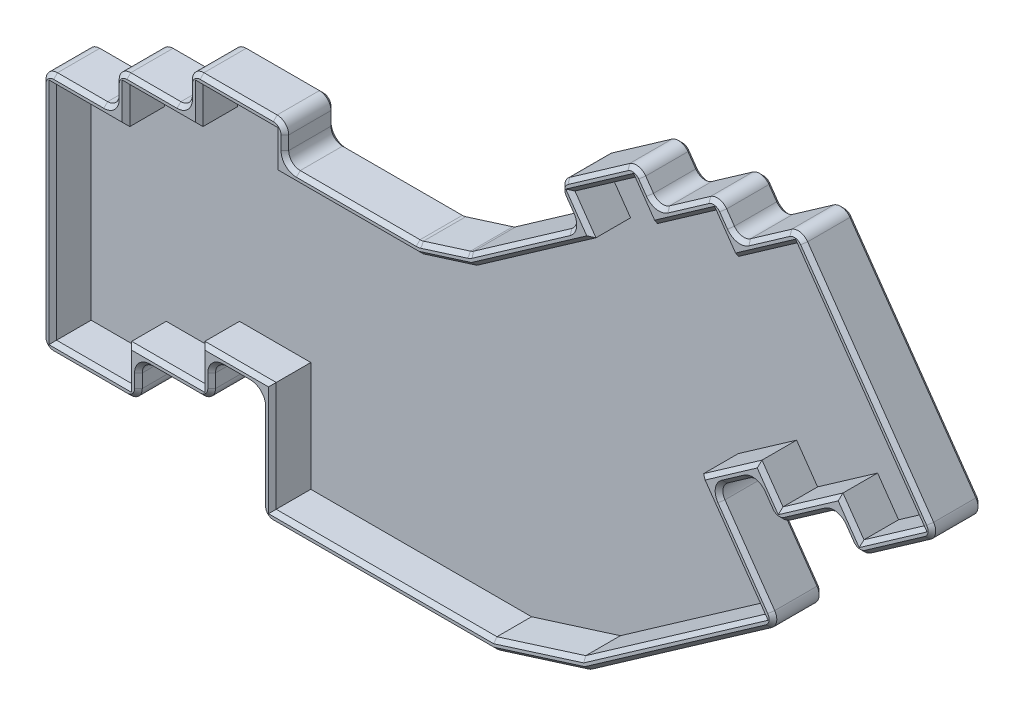
SolidWorks part; units mm, degrees
ref_plane "Front Plane" through (0, 0, 0) normal (0, 0, 1) x (1, 0, 0)
ref_plane "Top Plane" through (0, 0, 0) normal (0, 1, 0) x (1, 0, 0)
ref_plane "Right Plane" through (0, 0, 0) normal (1, 0, 0) x (0, 0, -1)
sketch "Sketch1" plane through (0, 0, 0) normal (0, 0, 1) x (1, 0, 0)
  line L64 (57.15, -66.675) -> (114.3, -66.675)
  line L65 (114.3, -66.675) -> (137.3388, -59.4109)
  line L66 (137.3388, -59.4109) -> (184.1534, -26.631)
  line L67 (184.1534, -26.631) -> (167.7634, -3.2237)
  line L68 (167.7634, -3.2237) -> (183.3683, 7.7029)
  line L69 (183.3683, 7.7029) -> (188.8316, -0.0995)
  line L70 (188.8316, -0.0995) -> (204.4364, 10.8271)
  line L71 (204.4364, 10.8271) -> (209.8998, 3.0247)
  line L72 (209.8998, 3.0247) -> (225.5046, 13.9513)
  line L73 (225.5046, 13.9513) -> (192.7247, 60.7659)
  line L74 (192.7247, 60.7659) -> (177.1199, 49.8392)
  line L75 (177.1199, 49.8392) -> (171.6565, 57.6417)
  line L76 (171.6565, 57.6417) -> (156.0517, 46.715)
  line L77 (156.0517, 46.715) -> (150.5884, 54.5175)
  line L78 (150.5884, 54.5175) -> (134.9835, 43.5908)
  line L79 (134.9835, 43.5908) -> (140.4469, 35.7884)
  line L80 (140.4469, 35.7884) -> (109.2372, 13.9351)
  line L81 (109.2372, 13.9351) -> (95.25, 9.525)
  line L82 (95.25, 9.525) -> (57.15, 9.525)
  line L83 (57.15, 9.525) -> (57.15, 19.05)
  line L84 (57.15, 19.05) -> (38.1, 19.05)
  line L85 (38.1, 19.05) -> (38.1, 9.525)
  line L86 (38.1, 9.525) -> (19.05, 9.525)
  line L87 (19.05, 9.525) -> (19.05, 0)
  line L88 (19.05, 0) -> (0, 0)
  line L89 (0, 0) -> (0, -57.15)
  line L90 (0, -57.15) -> (19.05, -57.15)
  line L91 (19.05, -57.15) -> (19.05, -47.625)
  line L92 (19.05, -47.625) -> (38.1, -47.625)
  line L93 (38.1, -47.625) -> (38.1, -38.1)
  line L94 (38.1, -38.1) -> (57.15, -38.1)
  line L95 (57.15, -38.1) -> (57.15, -66.675)
extrude "Boss-Extrude1" add sketch "Sketch1" along normal blind 3 contours L82 L83 L84 L85 L86 L87 L88 L89 L90 L91 L92 L93 L94 L95 L64 L65 L66 L67 L68 L69 L70 L71 L72 L73 L74 L75 L76 L77 L78 L79 L80 L81
sketch "Sketch2" plane through (0, 0, 3) normal (0, 0, 1) x (1, 0, 0)
  line L64 (107.8947, 16.6574) -> (94.7883, 12.525)
  line L65 (94.7883, 12.525) -> (60.15, 12.525)
  line L66 (60.15, 12.525) -> (60.15, 22.05)
  line L67 (60.15, 22.05) -> (35.1, 22.05)
  line L68 (35.1, 22.05) -> (35.1, 12.525)
  line L69 (35.1, 12.525) -> (16.05, 12.525)
  line L70 (16.05, 12.525) -> (16.05, 3)
  line L71 (16.05, 3) -> (-3, 3)
  line L72 (-3, 3) -> (-3, -60.15)
  line L73 (-3, -60.15) -> (22.05, -60.15)
  line L74 (22.05, -60.15) -> (22.05, -50.625)
  line L75 (22.05, -50.625) -> (41.1, -50.625)
  line L76 (41.1, -50.625) -> (41.1, -41.1)
  line L77 (41.1, -41.1) -> (54.15, -41.1)
  line L78 (54.15, -41.1) -> (54.15, -69.675)
  line L79 (54.15, -69.675) -> (114.7617, -69.675)
  line L80 (114.7617, -69.675) -> (138.6813, -62.1332)
  line L81 (138.6813, -62.1332) -> (188.3316, -27.3677)
  line L82 (188.3316, -27.3677) -> (171.9416, -3.9604)
  line L83 (171.9416, -3.9604) -> (182.6315, 3.5247)
  line L84 (182.6315, 3.5247) -> (188.0949, -4.2777)
  line L85 (188.0949, -4.2777) -> (203.6997, 6.6489)
  line L86 (203.6997, 6.6489) -> (209.163, -1.1535)
  line L87 (209.163, -1.1535) -> (229.6828, 13.2146)
  line L88 (229.6828, 13.2146) -> (193.4614, 64.9441)
  line L89 (193.4614, 64.9441) -> (177.8566, 54.0174)
  line L90 (177.8566, 54.0174) -> (172.3933, 61.8198)
  line L91 (172.3933, 61.8198) -> (156.7884, 50.8932)
  line L92 (156.7884, 50.8932) -> (151.3251, 58.6956)
  line L93 (151.3251, 58.6956) -> (130.8054, 44.3275)
  line L94 (130.8054, 44.3275) -> (136.2687, 36.5251)
  line L95 (136.2687, 36.5251) -> (107.8947, 16.6574)
  line L96 (107.8947, 16.6574) -> (94.7883, 12.525)
  line L97 (94.7883, 12.525) -> (60.15, 12.525)
  line L98 (60.15, 12.525) -> (60.15, 22.05)
  line L99 (60.15, 22.05) -> (35.1, 22.05)
  line L100 (35.1, 22.05) -> (35.1, 12.525)
  line L101 (35.1, 12.525) -> (16.05, 12.525)
  line L102 (16.05, 12.525) -> (16.05, 3)
  line L103 (16.05, 3) -> (-3, 3)
  line L104 (-3, 3) -> (-3, -60.15)
  line L105 (-3, -60.15) -> (22.05, -60.15)
  line L106 (22.05, -60.15) -> (22.05, -50.625)
  line L107 (22.05, -50.625) -> (41.1, -50.625)
  line L108 (41.1, -50.625) -> (41.1, -41.1)
  line L109 (41.1, -41.1) -> (54.15, -41.1)
  line L110 (54.15, -41.1) -> (54.15, -69.675)
  line L111 (54.15, -69.675) -> (114.7617, -69.675)
  line L112 (114.7617, -69.675) -> (138.6813, -62.1332)
  line L113 (138.6813, -62.1332) -> (188.3316, -27.3677)
  line L114 (188.3316, -27.3677) -> (171.9416, -3.9604)
  line L115 (171.9416, -3.9604) -> (182.6315, 3.5247)
  line L116 (182.6315, 3.5247) -> (188.0949, -4.2777)
  line L117 (188.0949, -4.2777) -> (203.6997, 6.6489)
  line L118 (203.6997, 6.6489) -> (209.163, -1.1535)
  line L119 (209.163, -1.1535) -> (229.6828, 13.2146)
  line L120 (229.6828, 13.2146) -> (193.4614, 64.9441)
  line L121 (193.4614, 64.9441) -> (177.8566, 54.0174)
  line L122 (177.8566, 54.0174) -> (172.3933, 61.8198)
  line L123 (172.3933, 61.8198) -> (156.7884, 50.8932)
  line L124 (156.7884, 50.8932) -> (151.3251, 58.6956)
  line L125 (151.3251, 58.6956) -> (130.8054, 44.3275)
  line L126 (130.8054, 44.3275) -> (136.2687, 36.5251)
  line L127 (136.2687, 36.5251) -> (107.8947, 16.6574)
  line L128 (109.2372, 13.9351) -> (95.25, 9.525)
  line L129 (95.25, 9.525) -> (57.15, 9.525)
  line L130 (57.15, 9.525) -> (57.15, 19.05)
  line L131 (57.15, 19.05) -> (38.1, 19.05)
  line L132 (38.1, 19.05) -> (38.1, 9.525)
  line L133 (38.1, 9.525) -> (19.05, 9.525)
  line L134 (19.05, 9.525) -> (19.05, 0)
  line L135 (19.05, 0) -> (0, 0)
  line L136 (0, 0) -> (0, -57.15)
  line L137 (0, -57.15) -> (19.05, -57.15)
  line L138 (19.05, -57.15) -> (19.05, -47.625)
  line L139 (19.05, -47.625) -> (38.1, -47.625)
  line L140 (38.1, -47.625) -> (38.1, -38.1)
  line L141 (38.1, -38.1) -> (57.15, -38.1)
  line L142 (57.15, -38.1) -> (57.15, -66.675)
  line L143 (57.15, -66.675) -> (114.3, -66.675)
  line L144 (114.3, -66.675) -> (137.3388, -59.4109)
  line L145 (137.3388, -59.4109) -> (184.1534, -26.631)
  line L146 (184.1534, -26.631) -> (167.7634, -3.2237)
  line L147 (167.7634, -3.2237) -> (183.3683, 7.7029)
  line L148 (183.3683, 7.7029) -> (188.8316, -0.0995)
  line L149 (188.8316, -0.0995) -> (204.4364, 10.8271)
  line L150 (204.4364, 10.8271) -> (209.8998, 3.0247)
  line L151 (209.8998, 3.0247) -> (225.5046, 13.9513)
  line L152 (225.5046, 13.9513) -> (192.7247, 60.7659)
  line L153 (192.7247, 60.7659) -> (177.1199, 49.8392)
  line L154 (177.1199, 49.8392) -> (171.6565, 57.6417)
  line L155 (171.6565, 57.6417) -> (156.0517, 46.715)
  line L156 (156.0517, 46.715) -> (150.5884, 54.5175)
  line L157 (150.5884, 54.5175) -> (134.9835, 43.5908)
  line L158 (134.9835, 43.5908) -> (140.4469, 35.7884)
  line L159 (140.4469, 35.7884) -> (109.2372, 13.9351)
  line L160 (109.2372, 13.9351) -> (95.25, 9.525)
  line L161 (95.25, 9.525) -> (57.15, 9.525)
  line L162 (57.15, 9.525) -> (57.15, 19.05)
  line L163 (57.15, 19.05) -> (38.1, 19.05)
  line L164 (38.1, 19.05) -> (38.1, 9.525)
  line L165 (38.1, 9.525) -> (19.05, 9.525)
  line L166 (19.05, 9.525) -> (19.05, 0)
  line L167 (19.05, 0) -> (0, 0)
  line L168 (0, 0) -> (0, -57.15)
  line L169 (0, -57.15) -> (19.05, -57.15)
  line L170 (19.05, -57.15) -> (19.05, -47.625)
  line L171 (19.05, -47.625) -> (38.1, -47.625)
  line L172 (38.1, -47.625) -> (38.1, -38.1)
  line L173 (38.1, -38.1) -> (57.15, -38.1)
  line L174 (57.15, -38.1) -> (57.15, -66.675)
  line L175 (57.15, -66.675) -> (114.3, -66.675)
  line L176 (114.3, -66.675) -> (137.3388, -59.4109)
  line L177 (137.3388, -59.4109) -> (184.1534, -26.631)
  line L178 (184.1534, -26.631) -> (167.7634, -3.2237)
  line L179 (167.7634, -3.2237) -> (183.3683, 7.7029)
  line L180 (183.3683, 7.7029) -> (188.8316, -0.0995)
  line L181 (188.8316, -0.0995) -> (204.4364, 10.8271)
  line L182 (204.4364, 10.8271) -> (209.8998, 3.0247)
  line L183 (209.8998, 3.0247) -> (225.5046, 13.9513)
  line L184 (225.5046, 13.9513) -> (192.7247, 60.7659)
  line L185 (192.7247, 60.7659) -> (177.1199, 49.8392)
  line L186 (177.1199, 49.8392) -> (171.6565, 57.6417)
  line L187 (171.6565, 57.6417) -> (156.0517, 46.715)
  line L188 (156.0517, 46.715) -> (150.5884, 54.5175)
  line L189 (150.5884, 54.5175) -> (134.9835, 43.5908)
  line L190 (134.9835, 43.5908) -> (140.4469, 35.7884)
  line L191 (140.4469, 35.7884) -> (109.2372, 13.9351)
  dimension "D1" = 3
  dimension "D2" = 0
extrude "Boss-Extrude2" add sketch "Sketch2" along normal blind 13 from surface at -3 starting at face at (106.2767, -1.0614, 0)
fillet "Fillet1" radius 3 32 edges at (114.7617, -69.675, 6.5) (94.7883, 12.525, 6.5) (60.15, 12.525, 6.5) (60.15, 22.05, 6.5) (35.1, 22.05, 6.5) (35.1, 12.525, 6.5) (16.05, 12.525, 6.5) (16.05, 3, 6.5) (-3, 3, 6.5) (-3, -60.15, 6.5) (22.05, -60.15, 6.5) (22.05, -50.625, 6.5) (41.1, -50.625, 6.5) (41.1, -41.1, 6.5) (54.15, -69.675, 6.5) (54.15, -41.1, 6.5) (107.8947, 16.6574, 6.5) (136.2687, 36.5251, 6.5) (130.8054, 44.3275, 6.5) (151.3251, 58.6956, 6.5) (156.7884, 50.8932, 6.5) (172.3933, 61.8198, 6.5) (177.8566, 54.0174, 6.5) (193.4614, 64.9441, 6.5) (229.6828, 13.2146, 6.5) (209.163, -1.1535, 6.5) (203.6997, 6.6489, 6.5) (188.0949, -4.2777, 6.5) (182.6315, 3.5247, 6.5) (171.9416, -3.9604, 6.5) (188.3316, -27.3677, 6.5) (138.6813, -62.1332, 6.5)
sketch "Sketch3" plane through (0, 0, 13) normal (0, 0, 1) x (1, 0, 0)
  line L32 (109.2372, 13.9351) -> (95.25, 9.525)
  line L33 (95.25, 9.525) -> (57.15, 9.525)
  line L34 (57.15, 9.525) -> (57.15, 19.05)
  line L35 (57.15, 19.05) -> (38.1, 19.05)
  line L36 (38.1, 19.05) -> (38.1, 9.525)
  line L37 (38.1, 9.525) -> (19.05, 9.525)
  line L38 (19.05, 9.525) -> (19.05, 0)
  line L39 (19.05, 0) -> (0, 0)
  line L40 (0, 0) -> (0, -57.15)
  line L41 (0, -57.15) -> (19.05, -57.15)
  line L42 (19.05, -57.15) -> (19.05, -47.625)
  line L43 (19.05, -47.625) -> (38.1, -47.625)
  line L44 (38.1, -47.625) -> (38.1, -38.1)
  line L45 (38.1, -38.1) -> (57.15, -38.1)
  line L46 (57.15, -38.1) -> (57.15, -66.675)
  line L47 (57.15, -66.675) -> (114.3, -66.675)
  line L48 (114.3, -66.675) -> (137.3388, -59.4109)
  line L49 (137.3388, -59.4109) -> (184.1534, -26.631)
  line L50 (184.1534, -26.631) -> (167.7634, -3.2237)
  line L51 (167.7634, -3.2237) -> (183.3683, 7.7029)
  line L52 (183.3683, 7.7029) -> (188.8316, -0.0995)
  line L53 (188.8316, -0.0995) -> (204.4364, 10.8271)
  line L54 (204.4364, 10.8271) -> (209.8998, 3.0247)
  line L55 (209.8998, 3.0247) -> (225.5046, 13.9513)
  line L56 (225.5046, 13.9513) -> (192.7247, 60.7659)
  line L57 (192.7247, 60.7659) -> (177.1199, 49.8392)
  line L58 (177.1199, 49.8392) -> (171.6565, 57.6417)
  line L59 (171.6565, 57.6417) -> (156.0517, 46.715)
  line L60 (156.0517, 46.715) -> (150.5884, 54.5175)
  line L61 (150.5884, 54.5175) -> (134.9835, 43.5908)
  line L62 (134.9835, 43.5908) -> (140.4469, 35.7884)
  line L63 (140.4469, 35.7884) -> (109.2372, 13.9351)
  line L64 (109.2372, 13.9351) -> (95.25, 9.525)
  line L65 (95.25, 9.525) -> (57.15, 9.525)
  line L66 (57.15, 9.525) -> (57.15, 19.05)
  line L67 (57.15, 19.05) -> (38.1, 19.05)
  line L68 (38.1, 19.05) -> (38.1, 9.525)
  line L69 (38.1, 9.525) -> (19.05, 9.525)
  line L70 (19.05, 9.525) -> (19.05, 0)
  line L71 (19.05, 0) -> (0, 0)
  line L72 (0, 0) -> (0, -57.15)
  line L73 (0, -57.15) -> (19.05, -57.15)
  line L74 (19.05, -57.15) -> (19.05, -47.625)
  line L75 (19.05, -47.625) -> (38.1, -47.625)
  line L76 (38.1, -47.625) -> (38.1, -38.1)
  line L77 (38.1, -38.1) -> (57.15, -38.1)
  line L78 (57.15, -38.1) -> (57.15, -66.675)
  line L79 (57.15, -66.675) -> (114.3, -66.675)
  line L80 (114.3, -66.675) -> (137.3388, -59.4109)
  line L81 (137.3388, -59.4109) -> (184.1534, -26.631)
  line L82 (184.1534, -26.631) -> (167.7634, -3.2237)
  line L83 (167.7634, -3.2237) -> (183.3683, 7.7029)
  line L84 (183.3683, 7.7029) -> (188.8316, -0.0995)
  line L85 (188.8316, -0.0995) -> (204.4364, 10.8271)
  line L86 (204.4364, 10.8271) -> (209.8998, 3.0247)
  line L87 (209.8998, 3.0247) -> (225.5046, 13.9513)
  line L88 (225.5046, 13.9513) -> (192.7247, 60.7659)
  line L89 (192.7247, 60.7659) -> (177.1199, 49.8392)
  line L90 (177.1199, 49.8392) -> (171.6565, 57.6417)
  line L91 (171.6565, 57.6417) -> (156.0517, 46.715)
  line L92 (156.0517, 46.715) -> (150.5884, 54.5175)
  line L93 (150.5884, 54.5175) -> (134.9835, 43.5908)
  line L94 (134.9835, 43.5908) -> (140.4469, 35.7884)
  line L95 (140.4469, 35.7884) -> (109.2372, 13.9351)
  dimension "D1" = 0
extrude "Cut-Extrude-Thin3" cut sketch "Sketch3" against normal up to surface (10 mm away) thin
chamfer "Chamfer1" distance 1 angle 45 160 edges at (135.0449, 36.7409, 0) (121.0421, 25.8633, 0) (121.0421, 25.8633, 13) (107.879, 16.6891, 0) (101.3415, 14.5912, 13) (101.3415, 14.5912, 0) (94.7829, 12.5599, 0) (78.7383, 12.525, 13) (78.7383, 12.525, 0) (61.0287, 13.4037, 0) (60.15, 17.2875, 13) (60.15, 17.2875, 0) (59.2713, 21.1713, 0) (47.625, 22.05, 13) (47.625, 22.05, 0) (35.9787, 21.1713, 0) (35.1, 17.2875, 13) (35.1, 17.2875, 0) (34.2213, 13.4037, 0) (25.575, 12.525, 13) (25.575, 12.525, 0) (16.9287, 11.6463, 0) (16.05, 7.7625, 13) (16.05, 7.7625, 0) (15.1713, 3.8787, 0) (6.525, 3, 13) (6.525, 3, 0) (-2.1213, 2.1213, 0) (-3, -28.575, 13) (-3, -28.575, 0) (-2.1213, -59.2713, 0) (9.525, -60.15, 13) (9.525, -60.15, 0) (21.1713, -59.2713, 0) (22.05, -55.3875, 13) (22.05, -55.3875, 0) (22.9287, -51.5037, 0) (31.575, -50.625, 13) (31.575, -50.625, 0) (40.2213, -49.7463, 0) (41.1, -45.8625, 13) (41.1, -45.8625, 0) (41.9787, -41.9787, 0) (47.625, -41.1, 13) (47.625, -41.1, 0) (53.2713, -41.9787, 0) (54.15, -55.3875, 0) (54.15, -55.3875, 13) (55.0287, -68.7963, 0) (85.725, -69.675, 0) (85.725, -69.675, 13) (114.7564, -69.6401, 0) (126.7215, -65.9041, 0) (126.7215, -65.9041, 13) (138.6657, -62.1015, 0) (162.4668, -45.4784, 0) (162.4668, -45.4784, 13) (187.1078, -27.1519, 0) (180.1366, -15.6641, 0) (180.1366, -15.6641, 13) (173.1654, -4.1762, 0) (177.2866, -0.2179, 0) (177.2866, -0.2179, 13) (182.4158, 2.301, 0) (185.3632, -0.3765, 0) (185.3632, -0.3765, 13) (188.3106, -3.0539, 0) (195.8973, 1.1856, 0) (195.8973, 1.1856, 13) (203.4839, 5.4252, 0) (206.4314, 2.7477, 0) (206.4314, 2.7477, 13) (209.3788, 0.0703, 0) (219.4229, 6.0306, 0) (219.4229, 6.0306, 13) (228.459, 13.4304, 0) (211.5721, 39.0793, 0) (211.5721, 39.0793, 13) (193.2457, 63.7203, 0) (185.659, 59.4807, 0) (185.659, 59.4807, 13) (178.0724, 55.2412, 0) (175.1249, 57.9186, 0) (175.1249, 57.9186, 13) (172.1775, 60.5961, 0) (164.5908, 56.3565, 0) (164.5908, 56.3565, 13) (157.0042, 52.117, 0) (154.0568, 54.7944, 0) (154.0568, 54.7944, 13) (151.1093, 57.4719, 0) (141.0652, 51.5116, 0) (141.0652, 51.5116, 13) (132.0291, 44.1118, 0) (133.537, 40.4263, 0) (133.537, 40.4263, 13) (151.1093, 57.4719, 13) (157.0042, 52.117, 13) (172.1775, 60.5961, 13) (178.0724, 55.2412, 13) (193.2457, 63.7203, 13) (228.459, 13.4304, 13) (209.3788, 0.0703, 13) (203.4839, 5.4252, 13) (188.3106, -3.0539, 13) (182.4158, 2.301, 13) (173.1654, -4.1762, 13) (187.1078, -27.1519, 13) (138.6657, -62.1015, 13) (114.7564, -69.6401, 13) (55.0287, -68.7963, 13) (53.2713, -41.9787, 13) (41.9787, -41.9787, 13) (40.2213, -49.7463, 13) (22.9287, -51.5037, 13) (21.1713, -59.2713, 13) (-2.1213, -59.2713, 13) (-2.1213, 2.1213, 13) (15.1713, 3.8787, 13) (16.9287, 11.6463, 13) (34.2213, 13.4037, 13) (35.9787, 21.1713, 13) (59.2713, 21.1713, 13) (61.0287, 13.4037, 13) (94.7829, 12.5599, 13) (107.879, 16.6891, 13) (135.0449, 36.7409, 13) (132.0291, 44.1118, 13) (76.3058, 9.775, 13) (57.4, 14.5375, 13) (47.625, 19.3, 13) (37.85, 14.5375, 13) (28.325, 9.775, 13) (18.8, 5.0125, 13) (9.275, 0.25, 13) (-0.25, -28.575, 13) (9.525, -57.4, 13) (19.3, -52.6375, 13) (28.825, -47.875, 13) (38.35, -43.1125, 13) (47.625, -38.35, 13) (56.9, -52.6375, 13) (85.6192, -66.925, 13) (125.8946, -63.2814, 13) (160.9761, -43.1651, 13) (176.3066, -14.9887, 13) (175.7092, 2.0348, 13) (186.0385, 3.4535, 13) (196.5726, 5.0156, 13) (207.1067, 6.5777, 13) (217.8456, 8.2832, 13) (209.3194, 37.502, 13) (184.9837, 55.6507, 13) (174.4496, 54.0886, 13) (163.9155, 52.5265, 13) (153.3814, 50.9644, 13) (142.6426, 49.2589, 13) (137.367, 39.751, 13) (124.612, 25.0059, 13) (102.1684, 11.9685, 13)
